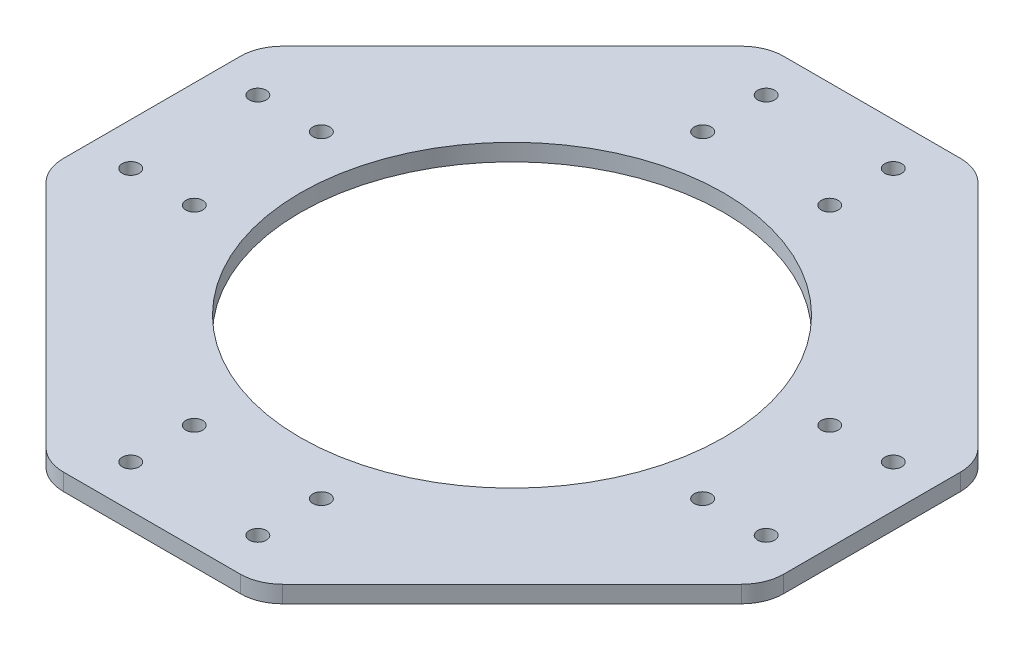
SolidWorks part; units mm, degrees
ref_plane "前视基准面" through (0, 0, 0) normal (0, 0, 1) x (1, 0, 0)
ref_plane "上视基准面" through (0, 0, 0) normal (0, 1, 0) x (1, 0, 0)
ref_plane "右视基准面" through (0, 0, 0) normal (1, 0, 0) x (0, 0, -1)
other "Configuration Table"
sketch "草图1" plane through (0, 0, 0) normal (0, 1, 0) x (1, 0, 0)
  line L0 (0, 0) -> (0, 85) construction
  line L1 (-85, 85) -> (85, 85)
  line L2 (-85, 85) -> (-85, -85)
  line L3 (-85, -85) -> (85, -85)
  line L4 (85, 85) -> (85, -85)
  line L5 (-25, 85) -> (-85, 25)
  line L6 (0, 0) -> (-85, 0) construction
  line L7 (-15, 75) -> (15, 75) construction
  line L8 (-75, 15) -> (-75, -15) construction
  line L9 (25, 85) -> (85, 25)
  line L10 (-25, -85) -> (-85, -25)
  line L11 (25, -85) -> (85, -25)
  line L12 (-15, 60) -> (15, 60) construction
  circle A25 centre (-15, 75) radius 2
  circle A26 centre (15, 75) radius 2
  circle A27 centre (0, 0) radius 50
  circle A28 centre (-75, 15) radius 2
  circle A29 centre (-75, -15) radius 2
  circle A30 centre (75, -15) radius 2
  circle A31 centre (75, 15) radius 2
  circle A32 centre (15, -75) radius 2
  circle A33 centre (-15, -75) radius 2
  circle A34 centre (-15, 60) radius 2
  circle A35 centre (15, 60) radius 2
  circle A36 centre (60, 15) radius 2
  circle A37 centre (60, -15) radius 2
  circle A38 centre (15, -60) radius 2
  circle A39 centre (-15, -60) radius 2
  circle A40 centre (-60, -15) radius 2
  circle A41 centre (-60, 15) radius 2
  point P14 (0, 75)
  point P18 (-75, 0)
  point P40 (0, 60)
  point P55 (0, 0)
  dimension "D3" = 60
  dimension "D1" = 170
  dimension "D4" = 4
  dimension "D6" = 10
  dimension "D7" = 4
  dimension "D8" = 30
  dimension "D10" = 100
  dimension "D12" = 4
  dimension "D2" = 45
  dimension "D5" = 30
  dimension "D9" = 10
  dimension "D11" = 30
  dimension "D13" = 60
extrude "凸台-拉伸1" add sketch "草图1" along normal blind 4 contours L3 L11 L4 L9 L1 L5 L2 L10 A32 A30 A29 A28 A27 A26 A25 A31 A33
fillet "圆角1" radius 10 8 edges at (-85, 2, 25) (-85, 2, -25) (-25, 2, -85) (25, 2, -85) (85, 2, -25) (85, 2, 25) (25, 2, 85) (-25, 2, 85)
